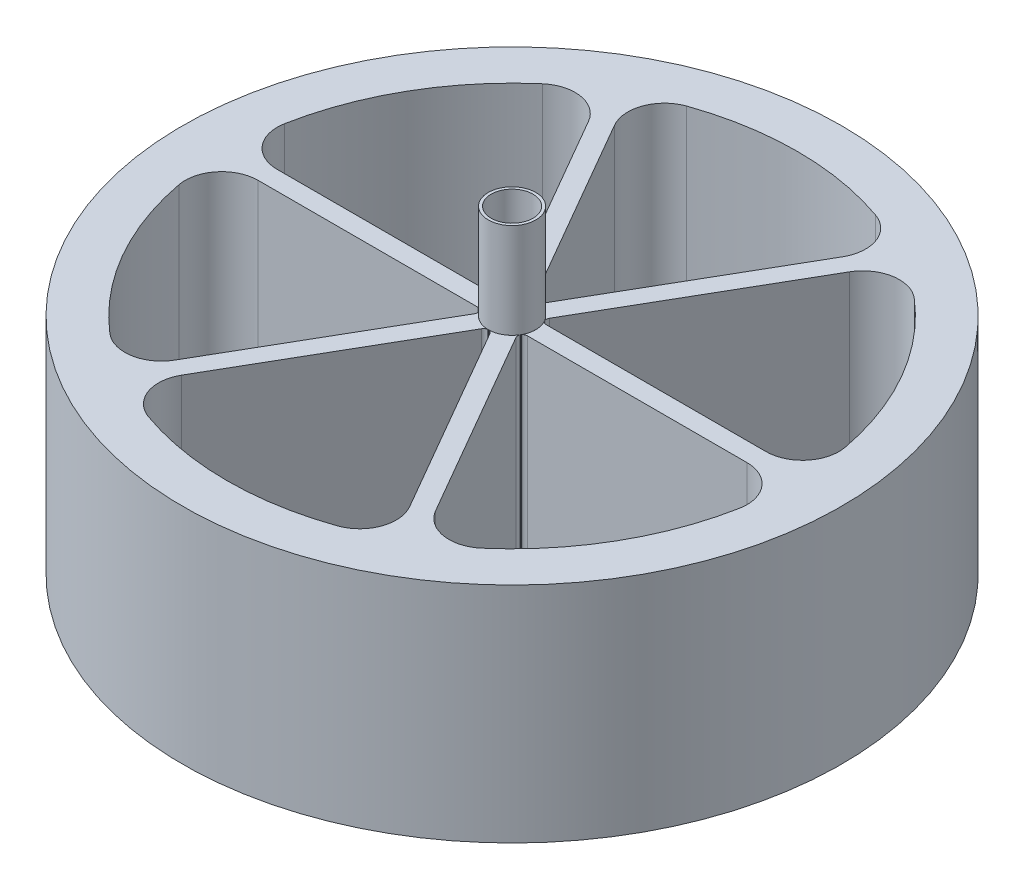
SolidWorks part; units mm, degrees
ref_plane "Front Plane" through (0, 0, 0) normal (0, 0, 1) x (1, 0, 0)
ref_plane "Top Plane" through (0, 0, 0) normal (0, 1, 0) x (1, 0, 0)
ref_plane "Right Plane" through (0, 0, 0) normal (1, 0, 0) x (0, 0, -1)
sketch "Sketch1" plane through (0, 0, 0) normal (0, 1, 0) x (1, 0, 0)
  circle A0 centre (0, 0) radius 2.2
  circle A1 centre (0, 0) radius 2.5
  dimension "D1" = 4.4
  dimension "D2" = 5
extrude "Boss-Extrude1" add sketch "Sketch1" along normal blind 10
sketch "Sketch2" plane through (0, 0, 0) normal (0, -1, 0) x (-1, 0, 0)
  line L1 (2.614, 1) -> (25.708, 1)
  line L2 (20.4475, 0) -> (20.4475, 1)
  line L3 (2.614, -1) -> (25.708, -1)
  line L4 (0.4409, -2.7637) -> (11.988, -22.7638)
  line L5 (2.173, -1.7637) -> (13.72, -21.7638)
  line L6 (-2.173, -1.7637) -> (-13.72, -21.7638)
  line L7 (-0.4409, -2.7637) -> (-11.988, -22.7638)
  line L8 (-2.614, 1) -> (-25.708, 1)
  line L9 (-2.614, -1) -> (-25.708, -1)
  line L10 (-0.4409, 2.7637) -> (-11.988, 22.7638)
  line L11 (-2.173, 1.7637) -> (-13.72, 21.7638)
  line L12 (2.173, 1.7637) -> (13.72, 21.7638)
  line L13 (0.4409, 2.7637) -> (11.988, 22.7638)
  line L14 (0.0941, -2.5116) -> (0.0272, -2.4999)
  line L15 (-0.0941, -2.5116) -> (-0.052, -2.4995)
  line L16 (2.2222, -1.1743) -> (2.1785, -1.2264)
  line L17 (2.128, -1.3373) -> (2.1386, -1.2947)
  line L18 (2.128, 1.3373) -> (2.1514, 1.2734)
  line L19 (2.2222, 1.1743) -> (2.1906, 1.2047)
  line L20 (-0.0941, 2.5116) -> (-0.0272, 2.4999)
  line L21 (0.0941, 2.5116) -> (0.052, 2.4995)
  line L22 (-2.2222, 1.1743) -> (-2.1785, 1.2264)
  line L23 (-2.128, 1.3373) -> (-2.1386, 1.2947)
  line L24 (-2.128, -1.3373) -> (-2.1514, -1.2734)
  line L25 (-2.2222, -1.1743) -> (-2.1906, -1.2047)
  arc A0 (9.9338, -28.3076) -> (19.5482, -22.7567) centre (0, 0) ccw
  arc A1 (25.708, 1) -> (29.482, 5.5509) centre (25.708, 4.8403) ccw
  circle A2 centre (0, 0) radius 2.5 construction
  arc A3 (2.2222, 1.1743) -> (2.614, 1) centre (2.614, 1.5276) ccw
  arc A4 (0.0272, -2.4999) -> (2.1386, -1.2947) centre (0, 0) ccw
  arc A5 (2.2222, -1.1743) -> (2.614, -1) centre (2.614, -1.5276) cw
  arc A6 (25.708, -1) -> (29.482, -5.5509) centre (25.708, -4.8403) cw
  arc A7 (2.128, -1.3373) -> (2.173, -1.7637) centre (2.6299, -1.5) ccw
  arc A8 (0.0941, -2.5116) -> (0.4409, -2.7637) centre (-0.0159, -3.0275) cw
  arc A9 (11.988, -22.7638) -> (9.9338, -28.3076) centre (8.6621, -24.6839) cw
  arc A10 (13.72, -21.7638) -> (19.5482, -22.7567) centre (17.0458, -19.8436) ccw
  arc A11 (-0.0941, -2.5116) -> (-0.4409, -2.7637) centre (0.0159, -3.0275) ccw
  arc A12 (-2.128, -1.3373) -> (-2.173, -1.7637) centre (-2.6299, -1.5) cw
  arc A13 (-13.72, -21.7638) -> (-19.5482, -22.7567) centre (-17.0458, -19.8436) cw
  arc A14 (-11.988, -22.7638) -> (-9.9338, -28.3076) centre (-8.6621, -24.6839) ccw
  arc A15 (-2.2222, -1.1743) -> (-2.614, -1) centre (-2.614, -1.5276) ccw
  arc A16 (-2.2222, 1.1743) -> (-2.614, 1) centre (-2.614, 1.5276) cw
  arc A17 (-25.708, 1) -> (-29.482, 5.5509) centre (-25.708, 4.8403) cw
  arc A18 (-25.708, -1) -> (-29.482, -5.5509) centre (-25.708, -4.8403) ccw
  arc A19 (-2.128, 1.3373) -> (-2.173, 1.7637) centre (-2.6299, 1.5) ccw
  arc A20 (-0.0941, 2.5116) -> (-0.4409, 2.7637) centre (0.0159, 3.0275) cw
  arc A21 (-11.988, 22.7638) -> (-9.9338, 28.3076) centre (-8.6621, 24.6839) cw
  arc A22 (-13.72, 21.7638) -> (-19.5482, 22.7567) centre (-17.0458, 19.8436) ccw
  arc A23 (0.0941, 2.5116) -> (0.4409, 2.7637) centre (-0.0159, 3.0275) ccw
  arc A24 (2.128, 1.3373) -> (2.173, 1.7637) centre (2.6299, 1.5) cw
  arc A25 (13.72, 21.7638) -> (19.5482, 22.7567) centre (17.0458, 19.8436) cw
  arc A26 (11.988, 22.7638) -> (9.9338, 28.3076) centre (8.6621, 24.6839) ccw
  arc A27 (-19.5482, -22.7567) -> (-9.9338, -28.3076) centre (0, 0) ccw
  arc A28 (-29.482, 5.5509) -> (-29.482, -5.5509) centre (0, 0) ccw
  arc A29 (-9.9338, 28.3076) -> (-19.5482, 22.7567) centre (0, 0) ccw
  arc A30 (19.5482, 22.7567) -> (9.9338, 28.3076) centre (0, 0) ccw
  arc A31 (29.482, -5.5509) -> (29.482, 5.5509) centre (0, 0) ccw
  arc A32 (-2.1514, -1.2734) -> (-0.052, -2.4995) centre (0, 0) ccw
  arc A33 (-2.1785, 1.2264) -> (-2.1906, -1.2047) centre (0, 0) ccw
  arc A34 (-0.0272, 2.4999) -> (-2.1386, 1.2947) centre (0, 0) ccw
  arc A35 (2.1514, 1.2734) -> (0.052, 2.4995) centre (0, 0) ccw
  arc A36 (2.1785, -1.2264) -> (2.1906, 1.2047) centre (0, 0) ccw
  point P85 (0, 0)
  point P108 (0, 0)
  dimension "D1" = 60
  dimension "D4" = 6
extrude "Boss-Extrude3" add sketch "Sketch2" along normal blind 23.5 separate body contours L6 A13 A27 A14 L7 A11 L15 A32 L24 A12 | L4 A9 A0 A10 L5 A7 L17 A4 L14 A8 | L1 A1 A31 A6 L3 A5 L16 A36 L19 A3 | L13 A26 A30 A25 L12 A24 L18 A35 L21 A23 | L11 A22 A29 A21 L10 A20 L20 A34 L23 A19 | L9 A18 A28 A17 L8 A16 L22 A33 L25 A15
sketch "Sketch5" plane through (0, -23.5, 0) normal (0, -1, 0) x (-1, 0, 0)
  circle A0 centre (0, 0) radius 30
  circle A1 centre (0, 0) radius 34.6666
extrude "Boss-Extrude4" add sketch "Sketch5" against normal blind 23.5
sketch "Sketch6" plane through (0, 10, 0) normal (0, 1, 0) x (1, 0, 0)
  circle A0 centre (0, 0) radius 1.5
extrude "Boss-Extrude5" add sketch "Sketch6" against normal blind 10
sketch "Sketch8" plane through (0, 10, 0) normal (0, 1, 0) x (1, 0, 0)
  circle A0 centre (0, 0) radius 1.5
extrude "Cut-Extrude2" cut sketch "Sketch8" against normal blind 10
